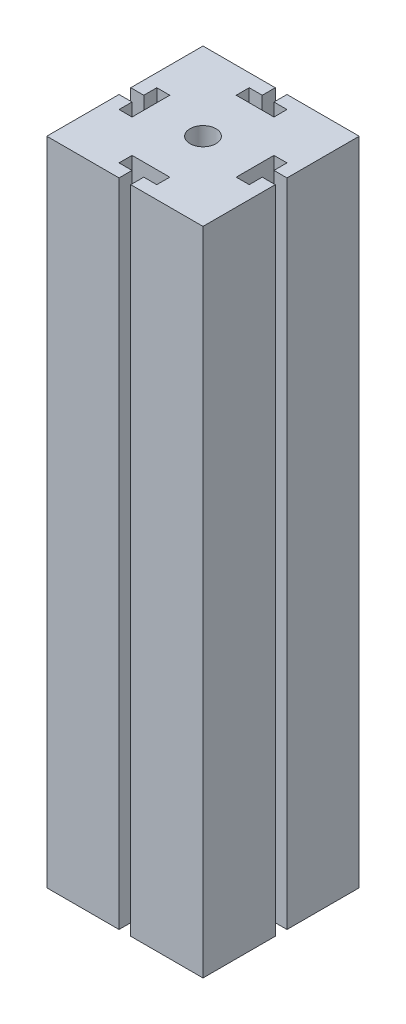
SolidWorks part; units mm, degrees
ref_plane "Plan de face" through (0, 0, 0) normal (0, 0, 1) x (1, 0, 0)
ref_plane "Plan de dessus" through (0, 0, 0) normal (0, 1, 0) x (1, 0, 0)
ref_plane "Plan de droite" through (0, 0, 0) normal (1, 0, 0) x (0, 0, -1)
sketch "Esquisse1" plane through (0, 0, 0) normal (0, 1, 0) x (1, 0, 0)
  line L1 (-6, 6) -> (6, 6)
  line L2 (-6, 6) -> (-6, -6)
  line L3 (-6, -6) -> (6, -6)
  line L4 (6, 6) -> (6, -6)
  dimension "D1" = 12
  dimension "D2" = 12
  dimension "D3" = 6
  dimension "D4" = 6
extrude "Boss.-Extru.1" add sketch "Esquisse1" along normal blind 50
sketch "Esquisse2" plane through (0, 50, 0) normal (0, 1, 0) x (1, 0, 0)
  line L0 (-5, -0.45) -> (-5, -1.45)
  line L1 (-6, 0.45) -> (-5, 0.45)
  line L2 (-6, 0.45) -> (-6, -0.45)
  line L3 (-6, -0.45) -> (-5, -0.45)
  line L5 (-5, 1.45) -> (-4, 1.45)
  line L6 (-5, 1.45) -> (-5, 0.45)
  line L7 (-5, -1.45) -> (-4, -1.45)
  line L8 (-4, 1.45) -> (-4, -1.45)
  line L9 (-6, 6) -> (-6, -6) construction
  line L10 (1.45, 5) -> (1.45, 4)
  line L11 (1.45, 4) -> (-1.45, 4)
  line L12 (-1.45, 5) -> (-1.45, 4)
  line L13 (-0.45, 5) -> (-1.45, 5)
  line L14 (-0.45, 6) -> (-0.45, 5)
  line L15 (0.45, 6) -> (-0.45, 6)
  line L16 (0.45, 6) -> (0.45, 5)
  line L17 (1.45, 5) -> (0.45, 5)
  line L18 (5, -1.45) -> (4, -1.45)
  line L19 (4, -1.45) -> (4, 1.45)
  line L20 (5, 1.45) -> (4, 1.45)
  line L21 (5, 0.45) -> (5, 1.45)
  line L22 (6, 0.45) -> (5, 0.45)
  line L23 (6, -0.45) -> (6, 0.45)
  line L24 (6, -0.45) -> (5, -0.45)
  line L25 (5, -1.45) -> (5, -0.45)
  line L26 (-1.45, -5) -> (-1.45, -4)
  line L27 (-1.45, -4) -> (1.45, -4)
  line L28 (1.45, -5) -> (1.45, -4)
  line L29 (0.45, -5) -> (1.45, -5)
  line L30 (0.45, -6) -> (0.45, -5)
  line L31 (-0.45, -6) -> (0.45, -6)
  line L32 (-0.45, -6) -> (-0.45, -5)
  line L33 (-1.45, -5) -> (-0.45, -5)
  point P38 (0, 0)
  dimension "D1" = 0.9
  dimension "D2" = 1
  dimension "D3" = 1
  dimension "D4" = 0
  dimension "D5" = 0.45
  dimension "D6" = 1
  dimension "D7" = 2
  dimension "D8" = 4
extrude "Enlèv. mat.-Extru.1" cut sketch "Esquisse2" against normal up to vertex (50 mm away) up to point (0, 0, 0)
sketch "Esquisse3" plane through (0, 50, 0) normal (0, 1, 0) x (1, 0, 0)
  circle A0 centre (0, 0) radius 1
  dimension "D1" = 2
extrude "Enlèv. mat.-Extru.2" cut sketch "Esquisse3" against normal blind 50
